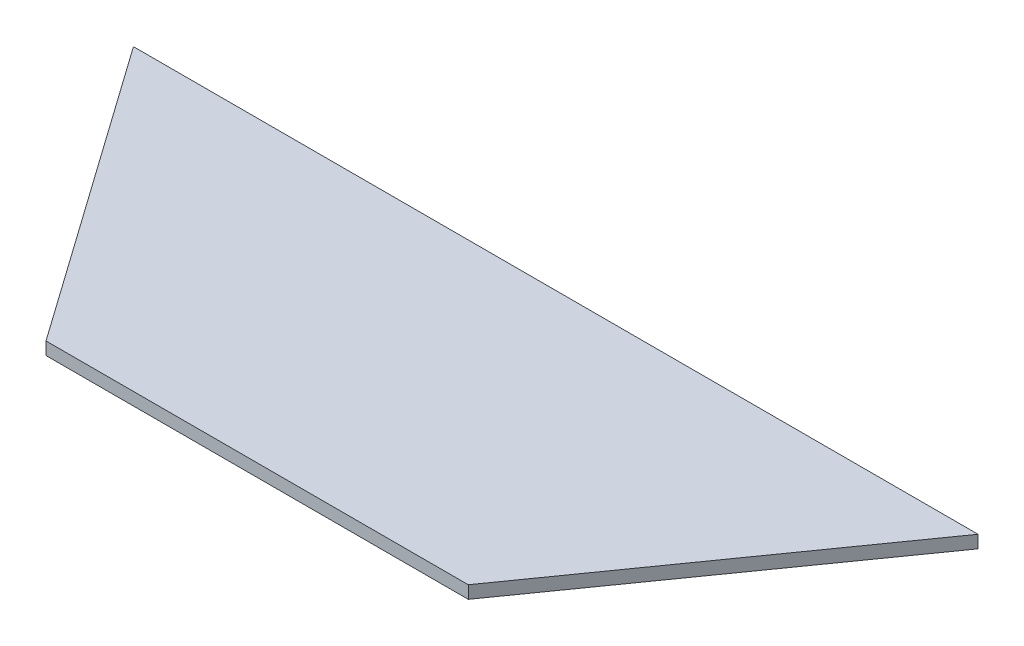
SolidWorks part; units mm, degrees
ref_plane "Front Plane" through (0, 0, 0) normal (0, 0, 1) x (1, 0, 0)
ref_plane "Top Plane" through (0, 0, 0) normal (0, 1, 0) x (1, 0, 0)
ref_plane "Right Plane" through (0, 0, 0) normal (1, 0, 0) x (0, 0, -1)
sketch "Sketch1" plane through (0, 0, 0) normal (0, 1, 0) x (1, 0, 0)
  line L0 (-50, 35.3553) -> (-25, 0)
  line L1 (50, 35.3553) -> (-50, 35.3553)
  line L3 (25, 0) -> (-25, 0)
  line L5 (50, 35.3553) -> (25, 0)
  line L6 (0, 0) -> (0, 35.3553) construction
  point P7 (122.9497, 92.3029)
  point P8 (-97.4972, 98.5009)
  point P9 (0, 35.3553)
  dimension "Base" = 50
  dimension "D1" = 100
  dimension "D2" = 35.3553
extrude "Boss-Extrude1" add sketch "Sketch1" along normal blind 1.5
equation "\"base\"=50"
equation "\"Base@Sketch1\"=\"base\""
equation "\"height\"= 60"
equation "\"angle\" = 45deg"
equation "\"width\" = 100"
equation "\"D1@Sketch1\"=\"width\""
equation "\"D2@Sketch1\"=(\"width\"-\"base\")/2/sin(\"angle\")"
